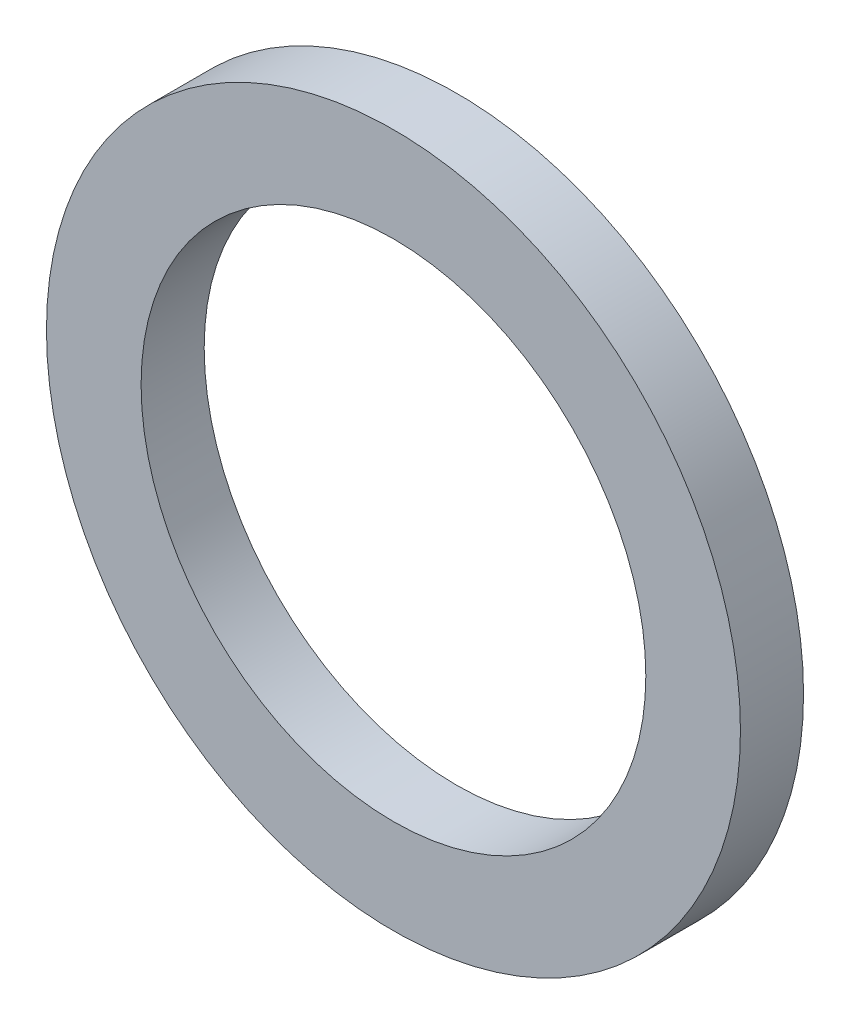
SolidWorks part; units mm, degrees
ref_plane "Front Plane" through (0, 0, 0) normal (0, 0, 1) x (1, 0, 0)
ref_plane "Top Plane" through (0, 0, 0) normal (0, 1, 0) x (1, 0, 0)
ref_plane "Right Plane" through (0, 0, 0) normal (1, 0, 0) x (0, 0, -1)
sketch "Sketch1" plane through (0, 0, 0) normal (0, 0, 1) x (1, 0, 0)
  circle A0 centre (0, 0) radius 8
  circle A1 centre (0, 0) radius 11
  dimension "D1" = 16
  dimension "D2" = 22
extrude "Boss-Extrude1" add sketch "Sketch1" along normal blind 2
